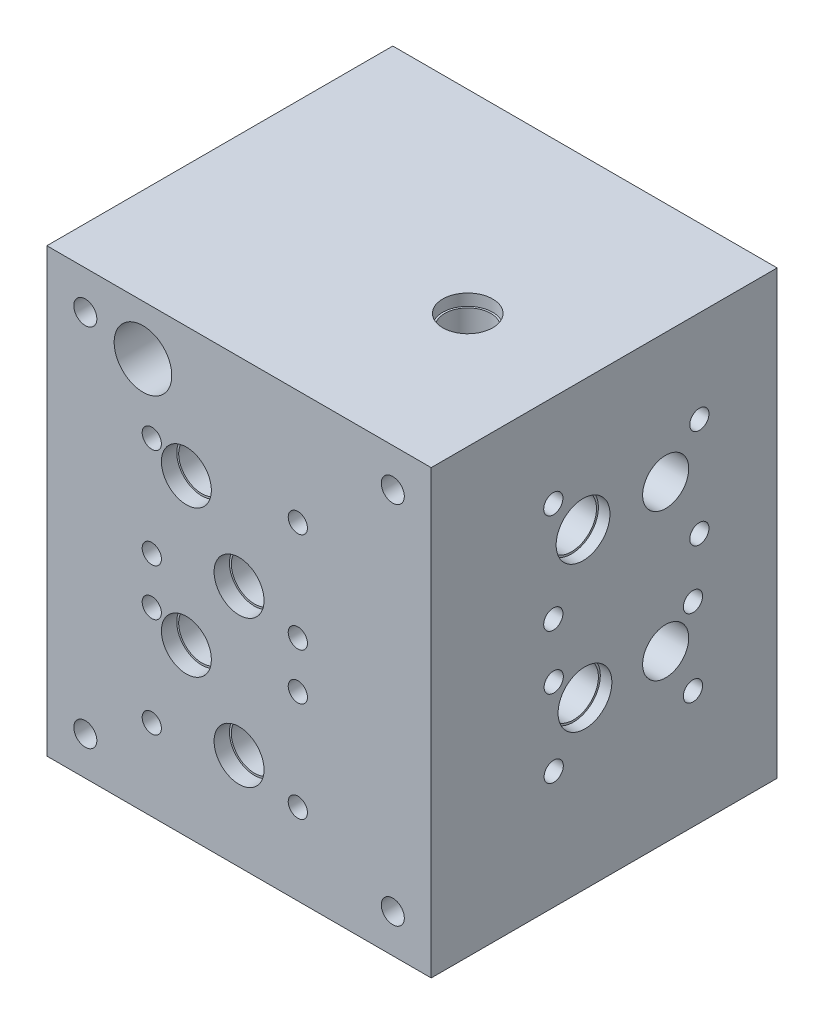
SolidWorks part; units mm, degrees
ref_plane "前视基准面" through (0, 0, 0) normal (0, 0, 1) x (1, 0, 0)
ref_plane "上视基准面" through (0, 0, 0) normal (0, 1, 0) x (1, 0, 0)
ref_plane "右视基准面" through (0, 0, 0) normal (1, 0, 0) x (0, 0, -1)
other "Configuration Table"
sketch "草图1" plane through (0, 0, 0) normal (0, 0, 1) x (1, 0, 0)
  line L1 (-100, -100) -> (100, -100)
  line L2 (-100, -100) -> (-100, 100)
  line L3 (-100, 100) -> (100, 100)
  line L4 (100, -100) -> (100, 100)
  line L5 (-100, -100) -> (100, 100) construction
  line L6 (-100, 100) -> (100, -100) construction
  point P0 (0, 0)
  dimension "D1" = 200
  dimension "D2" = 200
extrude "凸台-拉伸1" add sketch "草图1" along normal blind 180
sketch "草图2" plane through (0, 0, 0) normal (0, 0, -1) x (-1, 0, 0)
  line L0 (-100, -100) -> (-100, 100) construction
  line L3 (100, -100) -> (-100, -100) construction
  line L4 (100, 100) -> (100, -100) construction
  point P0 (-80, 110)
  point P1 (80, 110)
  point P2 (-80, -80)
  point P3 (80, -80)
  point P6 (50, 104)
  dimension "D1" = 20
  dimension "D2" = 210
  dimension "D3" = 210
  dimension "D4" = 20
  dimension "D5" = 20
  dimension "D6" = 20
  dimension "D7" = 20
  dimension "D8" = 20
  dimension "D9" = 50
  dimension "D10" = 204
hole_wizard "M14 螺纹孔1" positions "草图3" profile "草图5" tap size "M14" standard "GB" end condition through all
sketch "草图3" plane through (0, 0, 0) normal (0, 0, -1) x (-1, 0, 0)
  point P0 (-80, 110)
  point P3 (80, 110)
  point P6 (80, -80)
  point P9 (-80, -80)
sketch "草图5" plane through (80, 110, 0) normal (1, 0, 0) x (0, 1, 0)
  line L0 (0, 0) -> (0, 180)
  line L1 (0, 180) -> (6, 180)
  line L2 (6, 180) -> (6, 0)
  line L5 (6, 0) -> (0, 0)
  line L11 (0, -6.35) -> (0, 107.95) construction
  dimension "通孔螺纹孔钻头直径" = 12
  dimension "通孔螺纹孔钻头深度" = 180
cosmetic thread "孔螺蚊线1" parameters "D2"=14
cosmetic thread "孔螺蚊线2" parameters "D2"=14
sketch "草图9" plane through (0, 0, 0) normal (0, 0, -1) x (-1, 0, 0)
  line L0 (100, -100) -> (-100, -100) construction
  line L2 (-100, -100) -> (-100, 100) construction
  point P0 (0, -70)
  dimension "D1" = 30
  dimension "D2" = 100
hole_wizard "M14 六角头螺栓的柱形沉头孔2" positions "草图19" profile "草图20" counterbore size "M14" standard "GB"
sketch "草图19" plane through (0, 0, 0) normal (0, 0, -1) x (-1, 0, 0)
  point P0 (0, -70)
sketch "草图20" plane through (0, -70, 0) normal (1, 0, 0) x (0, 1, 0)
  line L0 (0, 0) -> (0, 68)
  line L1 (0, 68) -> (12, 60.7897)
  line L2 (12, 60.7897) -> (12, 8)
  line L3 (12, 8) -> (13, 8)
  line L4 (13, 8) -> (13, 0)
  line L5 (13, 0) -> (0, 0)
  line L10 (0, 68) -> (-12, 60.7897) construction
  line L11 (0, -6.35) -> (0, 107.95) construction
  dimension "孔直径" = 24
  dimension "孔深度" = 68
  dimension "柱形沉头孔直径" = 26
  dimension "柱形沉头孔深度" = 8
  dimension "导头角度" = 118
sketch "草图21" plane through (0, -100, 0) normal (0, -1, 0) x (1, 0, 0)
  point P0 (0, 49.309)
hole_wizard "M16 六角头螺栓的柱形沉头孔2" positions "草图22" profile "草图23" counterbore size "M16" standard "GB"
sketch "草图22" plane through (0, -100, 0) normal (0, -1, 0) x (-1, 0, 0)
  point P0 (0, -49.309)
sketch "草图23" plane through (0, -100, 49.309) normal (1, 0, 0) x (0, 0, -1)
  line L0 (0, 0) -> (0, 40)
  line L1 (0, 40) -> (11, 33.3905)
  line L2 (11, 33.3905) -> (11, 6)
  line L3 (11, 6) -> (12, 6)
  line L4 (12, 6) -> (12, 0)
  line L5 (12, 0) -> (0, 0)
  line L10 (0, 40) -> (-11, 33.3905) construction
  line L11 (0, -6.35) -> (0, 107.95) construction
  dimension "孔直径" = 22
  dimension "孔深度" = 40
  dimension "柱形沉头孔直径" = 24
  dimension "柱形沉头孔深度" = 6
  dimension "导头角度" = 118
sketch "草图24" plane through (0, -100, 0) normal (0, -1, 0) x (1, 0, 0)
  line L0 (-100, 180) -> (-100, 0) construction
  line L1 (100, 180) -> (100, 0) construction
  line L2 (-100, 0) -> (100, 0) construction
  point P0 (-52, 80)
  point P1 (52, 80)
  point P8 (-52, 35)
  point P9 (52, 35)
  point P10 (0, 89.309)
  dimension "D1" = 48
  dimension "D2" = 48
  dimension "D3" = 80
  dimension "D4" = 80
  dimension "D5" = 45
  dimension "D6" = 45
  dimension "D7" = 40
hole_wizard "M12 螺纹孔1" positions "草图25" profile "草图26" tap size "M12" standard "GB"
sketch "草图25" plane through (0, -100, 0) normal (0, -1, 0) x (-1, 0, 0)
  point P0 (-52, -80)
  point P3 (52, -80)
  point P6 (52, -35)
  point P9 (-52, -35)
cosmetic thread "孔螺蚊线5" parameters "D1"=24, "D2"=12
cosmetic thread "孔螺蚊线6" parameters "D1"=24, "D2"=12
cosmetic thread "孔螺蚊线7" parameters "D1"=24, "D2"=12
cosmetic thread "孔螺蚊线8" parameters "D1"=24, "D2"=12
sketch "草图26" plane through (52, -100, 80) normal (1, 0, 0) x (0, 0, -1)
  line L0 (0, 0) -> (0, 20)
  line L1 (0, 20) -> (5.1, 16.9356)
  line L2 (5.1, 16.9356) -> (5.1, 0)
  line L5 (5.1, 0) -> (0, 0)
  line L10 (0, 20) -> (-5.1, 16.9356) construction
  line L11 (0, -6.35) -> (0, 107.95) construction
  dimension "螺纹孔钻头直径" = 10.2
  dimension "螺纹孔钻头深度" = 20
  dimension "导头角度" = 118
hole_wizard "M16 六角头螺栓的柱形沉头孔3" positions "草图28" profile "草图29" counterbore size "M16" standard "GB"
sketch "草图28" plane through (0, -100, 0) normal (0, -1, 0) x (-1, 0, 0)
  point P0 (0, -89.309)
sketch "草图29" plane through (0, -100, 89.309) normal (1, 0, 0) x (0, 0, -1)
  line L0 (0, 0) -> (0, 144)
  line L1 (0, 144) -> (12, 136.7897)
  line L2 (12, 136.7897) -> (12, 6)
  line L3 (12, 6) -> (13, 6)
  line L4 (13, 6) -> (13, 0)
  line L5 (13, 0) -> (0, 0)
  line L10 (0, 144) -> (-12, 136.7897) construction
  line L11 (0, -6.35) -> (0, 107.95) construction
  dimension "孔直径" = 24
  dimension "孔深度" = 144
  dimension "柱形沉头孔直径" = 26
  dimension "柱形沉头孔深度" = 6
  dimension "导头角度" = 118
sketch "草图31" plane through (0, 0, 180) normal (0, 0, 1) x (1, 0, 0)
  line L1 (-52.4052, 77.5676) -> (37.5948, 77.5676)
  line L2 (-52.4052, 77.5676) -> (-52.4052, 11.5676)
  line L3 (-52.4052, 11.5676) -> (37.5948, 11.5676)
  line L4 (37.5948, 77.5676) -> (37.5948, 11.5676)
  line L5 (-52.4052, 1.2935) -> (37.5948, 1.2935)
  line L6 (-52.4052, 1.2935) -> (-52.4052, -64.7065)
  line L7 (-52.4052, -64.7065) -> (37.5948, -64.7065)
  line L8 (37.5948, 1.2935) -> (37.5948, -64.7065)
  point P8 (-45.4052, 70.5676)
  point P9 (30.5948, 70.5676)
  point P10 (-45.4052, 18.5676)
  point P11 (30.5948, 18.5676)
  point P12 (30.5948, -5.7065)
  point P13 (30.5948, -57.7065)
  point P14 (-45.4052, -57.7065)
  point P15 (0, -49.7065)
  point P16 (-45.4052, -5.7065)
  point P17 (-27.4052, -13.7065)
  point P18 (0, 26.5676)
  point P19 (-27.4052, 62.5676)
  dimension "D1" = 66
  dimension "D2" = 66
  dimension "D3" = 90
  dimension "D4" = 90
  dimension "D5" = 7
  dimension "D6" = 7
  dimension "D7" = 7
  dimension "D8" = 7
  dimension "D9" = 7
  dimension "D10" = 7
  dimension "D11" = 7
  dimension "D12" = 7
  dimension "D13" = 7
  dimension "D14" = 7
  dimension "D15" = 7
  dimension "D16" = 7
  dimension "D17" = 15
  dimension "D18" = 15
  dimension "D19" = 15
  dimension "D20" = 15
  dimension "D21" = 25
  dimension "D22" = 25
hole_wizard "M12 螺纹孔2" positions "草图32" profile "草图33" tap size "M12" standard "GB"
sketch "草图32" plane through (0, 0, 180) normal (0, 0, 1) x (1, 0, 0)
  point P0 (-45.4052, 70.5676)
  point P3 (30.5948, 70.5676)
  point P6 (30.5948, 18.5676)
  point P9 (-45.4052, 18.5676)
  point P12 (-45.4052, -5.7065)
  point P15 (-45.4052, -57.7065)
  point P18 (30.5948, -5.7065)
  point P21 (30.5948, -57.7065)
sketch "草图33" plane through (-45.4052, 70.5676, 180) normal (1, 0, 0) x (0, -1, 0)
  line L0 (0, 0) -> (0, 20)
  line L1 (0, 20) -> (5, 16.9957)
  line L2 (5, 16.9957) -> (5, 0)
  line L5 (5, 0) -> (0, 0)
  line L10 (0, 20) -> (-5, 16.9957) construction
  line L11 (0, -6.35) -> (0, 107.95) construction
  dimension "螺纹孔钻头直径" = 10
  dimension "螺纹孔钻头深度" = 20
  dimension "导头角度" = 118
cosmetic thread "孔螺蚊线9" parameters "D1"=24, "D2"=12
cosmetic thread "孔螺蚊线10" parameters "D1"=24, "D2"=12
cosmetic thread "孔螺蚊线11" parameters "D1"=24, "D2"=12
cosmetic thread "孔螺蚊线12" parameters "D1"=24, "D2"=12
cosmetic thread "孔螺蚊线13" parameters "D1"=24, "D2"=12
cosmetic thread "孔螺蚊线14" parameters "D1"=24, "D2"=12
cosmetic thread "孔螺蚊线15" parameters "D1"=24, "D2"=12
cosmetic thread "孔螺蚊线16" parameters "D1"=24, "D2"=12
hole_wizard "M14 六角头螺栓的柱形沉头孔3" positions "草图40" profile "草图41" counterbore size "M14" standard "GB"
sketch "草图40" plane through (0, 0, 180) normal (0, 0, 1) x (1, 0, 0)
  point P0 (0, -49.7065)
  point P6 (0, 26.5676)
sketch "草图41" plane through (0, -49.7065, 180) normal (1, 0, 0) x (0, -1, 0)
  line L0 (0, 0) -> (0, 98)
  line L1 (0, 98) -> (12, 90.7897)
  line L2 (12, 90.7897) -> (12, 8)
  line L3 (12, 8) -> (13, 8)
  line L4 (13, 8) -> (13, 0)
  line L5 (13, 0) -> (0, 0)
  line L10 (0, 98) -> (-12, 90.7897) construction
  line L11 (0, -6.35) -> (0, 107.95) construction
  dimension "孔直径" = 24
  dimension "孔深度" = 98
  dimension "柱形沉头孔直径" = 26
  dimension "柱形沉头孔深度" = 8
  dimension "导头角度" = 118
hole_wizard "M14 六角头螺栓的柱形沉头孔4" positions "草图42" profile "草图43" counterbore size "M14" standard "GB"
sketch "草图42" plane through (0, 0, 180) normal (0, 0, 1) x (1, 0, 0)
  point P0 (-27.4052, 62.5676)
  point P3 (-27.4052, -13.7065)
sketch "草图43" plane through (-27.4052, 62.5676, 180) normal (1, 0, 0) x (0, -1, 0)
  line L0 (0, 0) -> (0, 78)
  line L1 (0, 78) -> (12, 70.7897)
  line L2 (12, 70.7897) -> (12, 8)
  line L3 (12, 8) -> (13, 8)
  line L4 (13, 8) -> (13, 0)
  line L5 (13, 0) -> (0, 0)
  line L10 (0, 78) -> (-12, 70.7897) construction
  line L11 (0, -6.35) -> (0, 107.95) construction
  dimension "孔直径" = 24
  dimension "孔深度" = 78
  dimension "柱形沉头孔直径" = 26
  dimension "柱形沉头孔深度" = 8
  dimension "导头角度" = 118
sketch "草图44" plane through (-100, 0, 0) normal (-1, 0, 0) x (0, 0, 1)
  line L0 (180, 77.5676) -> (180, 11.5676) construction
  line L1 (180, 1.2935) -> (180, -64.7065) construction
  point P0 (113, 62.5676)
  point P1 (113, -13.7065)
  dimension "D1" = 67
  dimension "D2" = 67
hole_wizard "M16 六角头螺栓的柱形沉头孔4" positions "草图45" profile "草图46" counterbore size "M16" standard "GB"
sketch "草图45" plane through (-100, 0, 0) normal (-1, 0, 0) x (0, 0, 1)
  point P0 (113, 62.5676)
  point P3 (113, -13.7065)
sketch "草图46" plane through (-100, 62.5676, 113) normal (0, 1, 0) x (0, 0, 1)
  line L0 (0, 0) -> (0, 90)
  line L1 (0, 90) -> (12, 82.7897)
  line L2 (12, 82.7897) -> (12, 6)
  line L3 (12, 6) -> (13, 6)
  line L4 (13, 6) -> (13, 0)
  line L5 (13, 0) -> (0, 0)
  line L10 (0, 90) -> (-12, 82.7897) construction
  line L11 (0, -6.35) -> (0, 107.95) construction
  dimension "孔直径" = 24
  dimension "孔深度" = 90
  dimension "柱形沉头孔直径" = 26
  dimension "柱形沉头孔深度" = 6
  dimension "导头角度" = 118
sketch "草图47" plane through (0, 100, 0) normal (0, 1, 0) x (1, 0, 0)
  line L1 (-100, 0) -> (100, 0)
  line L2 (-100, 0) -> (-100, -180)
  line L3 (-100, -180) -> (100, -180)
  line L4 (100, 0) -> (100, -180)
sketch "草图48" plane through (0, 100, 0) normal (0, 1, 0) x (1, 0, 0)
  line L1 (-100, 0) -> (100, 0)
  line L2 (-100, 0) -> (-100, -180)
  line L3 (-100, -180) -> (100, -180)
  line L4 (100, 0) -> (100, -180)
extrude "凸台-拉伸3" add sketch "草图48" along normal blind 30
hole_wizard "M14 螺纹孔2" positions "草图49" profile "草图50" tap size "M14" standard "GB" end condition through all
sketch "草图49" plane through (0, 0, 0) normal (0, 0, -1) x (-1, 0, 0)
  point P0 (-80, 110)
  point P3 (80, 110)
sketch "草图50" plane through (80, 110, 0) normal (1, 0, 0) x (0, 1, 0)
  line L0 (0, 0) -> (0, 180)
  line L1 (0, 180) -> (6, 180)
  line L2 (6, 180) -> (6, 0)
  line L5 (6, 0) -> (0, 0)
  line L11 (0, -6.35) -> (0, 107.95) construction
  dimension "通孔螺纹孔钻头直径" = 12
  dimension "通孔螺纹孔钻头深度" = 180
cosmetic thread "孔螺蚊线17" parameters "D2"=14
cosmetic thread "孔螺蚊线18" parameters "D2"=14
hole_wizard "M14 六角头螺栓的柱形沉头孔6" positions "草图53" profile "草图54" counterbore size "M14" standard "GB" end condition through all
sketch "草图53" plane through (0, 0, 0) normal (0, 0, -1) x (-1, 0, 0)
  point P0 (50, 104)
sketch "草图54" plane through (-50, 104, 0) normal (1, 0, 0) x (0, 1, 0)
  line L0 (0, 0) -> (0, 180)
  line L1 (0, 180) -> (15, 180)
  line L3 (15, 180) -> (15, 14)
  line L4 (15, 14) -> (17, 14)
  line L5 (17, 14) -> (17, 0)
  line L7 (17, 0) -> (0, 0)
  line L11 (0, -6.35) -> (0, 107.95) construction
  dimension "通孔孔直径" = 30
  dimension "通孔孔深度" = 180
  dimension "柱形沉头孔直径" = 34
  dimension "柱形沉头孔深度" = 14
sketch "草图55" plane through (-100, 0, 0) normal (-1, 0, 0) x (0, 0, 1)
  point P0 (58, 62.5676)
  point P1 (58, -13.7065)
  dimension "D1" = 55
  dimension "D2" = 55
hole_wizard "M16 六角头螺栓的柱形沉头孔5" positions "草图56" profile "草图57" counterbore size "M16" standard "GB" end condition through all
sketch "草图56" plane through (-100, 0, 0) normal (-1, 0, 0) x (0, 0, 1)
  point P0 (58, 62.5676)
  point P3 (58, -13.7065)
sketch "草图57" plane through (-100, 62.5676, 58) normal (0, 1, 0) x (0, 0, 1)
  line L0 (0, 0) -> (0, 200)
  line L1 (0, 200) -> (12, 200)
  line L3 (12, 200) -> (12, 6)
  line L4 (12, 6) -> (13, 6)
  line L5 (13, 6) -> (13, 0)
  line L7 (13, 0) -> (0, 0)
  line L11 (0, -6.35) -> (0, 107.95) construction
  dimension "通孔孔直径" = 24
  dimension "通孔孔深度" = 200
  dimension "柱形沉头孔直径" = 26
  dimension "柱形沉头孔深度" = 6
sketch "草图60" plane through (-100, 0, 0) normal (-1, 0, 0) x (0, 0, 1)
  line L1 (136.144, -45.6939) -> (36.7889, -45.6939)
  line L2 (136.144, -45.6939) -> (136.144, 85.2553)
  line L3 (136.144, 85.2553) -> (36.7889, 85.2553)
  line L4 (36.7889, -45.6939) -> (36.7889, 85.2553)
  line L5 (136.144, -45.6939) -> (36.7889, 85.2553) construction
  line L6 (136.144, 85.2553) -> (36.7889, -45.6939) construction
  point P0 (86.4664, 19.7807)
sketch "草图61" plane through (100, 0, 0) normal (1, 0, 0) x (0, 0, -1)
  arc A0 (-123.1949, 56.238) -> (-123.1949, 68.8973) centre (-113, 62.5676) ccw construction
  arc A1 (-123.1949, -20.0361) -> (-123.1949, -7.3768) centre (-113, -13.7065) ccw construction
  point P0 (-101, 62.5676)
  point P1 (-101, -13.7065)
hole_wizard "M16 六角头螺栓的柱形沉头孔6" positions "草图62" profile "草图63" counterbore size "M16" standard "GB"
sketch "草图62" plane through (100, 0, 0) normal (1, 0, 0) x (0, 0, -1)
  circle A0 centre (-113, -13.7065) radius 13 construction
  point P0 (-101, 62.5676)
  point P3 (-100, -13.7065)
sketch "草图63" plane through (100, 62.5676, 101) normal (0, 1, 0) x (0, 0, -1)
  line L0 (0, 0) -> (0, 80)
  line L1 (0, 80) -> (13, 72.1888)
  line L2 (13, 72.1888) -> (13, 6)
  line L3 (13, 6) -> (14, 6)
  line L4 (14, 6) -> (14, 0)
  line L5 (14, 0) -> (0, 0)
  line L10 (0, 80) -> (-13, 72.1888) construction
  line L11 (0, -6.35) -> (0, 107.95) construction
  dimension "孔直径" = 26
  dimension "孔深度" = 80
  dimension "柱形沉头孔直径" = 28
  dimension "柱形沉头孔深度" = 6
  dimension "导头角度" = 118
sketch "草图64" plane through (100, 0, 0) normal (1, 0, 0) x (0, 0, -1)
  line L0 (-180, 89) -> (-14, 89) construction
  line L1 (-33.4648, 23) -> (-123.4648, 23)
  line L2 (-33.4648, 23) -> (-33.4648, 89)
  line L3 (-33.4648, 89) -> (-123.4648, 89)
  line L4 (-123.4648, 23) -> (-123.4648, 89)
  line L5 (-33.4648, 23) -> (-123.4648, 89) construction
  line L6 (-33.4648, 89) -> (-123.4648, 23) construction
  line L7 (-136.144, -45.6939) -> (-36.7889, -45.6939) construction
  line L8 (-33.2553, -57.4435) -> (-123.2553, -57.4435)
  line L9 (-33.2553, -57.4435) -> (-33.2553, 8.5565)
  line L10 (-33.2553, 8.5565) -> (-123.2553, 8.5565)
  line L11 (-123.2553, -57.4435) -> (-123.2553, 8.5565)
  line L12 (-33.2553, -57.4435) -> (-123.2553, 8.5565) construction
  line L13 (-33.2553, 8.5565) -> (-123.2553, -57.4435) construction
  line L14 (-36.7889, -45.6939) -> (-36.7889, 85.2553) construction
  point P0 (-78.4648, 56)
  point P7 (-78.2553, -24.4435)
  point P12 (-116.4648, 82)
  point P13 (-116.4648, 30)
  point P14 (-40.4648, 30.4949)
  point P15 (-40.4648, 82)
  point P16 (-116.2553, 1.5565)
  point P17 (-43.7889, 1.5565)
  point P18 (-116.2553, -38.6939)
  point P19 (-43.7889, -38.6939)
  dimension "D1" = 90
  dimension "D2" = 66
  dimension "D3" = 90
  dimension "D4" = 66
  dimension "D5" = 7
  dimension "D6" = 7
  dimension "D7" = 7
  dimension "D8" = 7.4949
  dimension "D9" = 7
  dimension "D10" = 7
  dimension "D11" = 7
  dimension "D12" = 7
  dimension "D13" = 7
  dimension "D14" = 7
  dimension "D15" = 7
  dimension "D16" = 7
  dimension "D17" = 7
  dimension "D18" = 7
  dimension "D19" = 7
hole_wizard "M12 螺纹孔3" positions "草图65" profile "草图66" tap size "M12" standard "GB"
sketch "草图65" plane through (100, 0, 0) normal (1, 0, 0) x (0, 0, -1)
  point P0 (-116.4648, 30)
  point P3 (-116.4648, 82)
  point P6 (-40.4648, 82)
  point P9 (-40.4648, 30.4949)
  point P12 (-43.7889, -38.6939)
  point P15 (-116.2553, -38.6939)
  point P18 (-116.2553, 1.5565)
  point P21 (-43.7889, 1.5565)
sketch "草图66" plane through (100, 30, 116.4648) normal (0, 1, 0) x (0, 0, -1)
  line L0 (0, 0) -> (0, 32.75)
  line L1 (0, 32.75) -> (5, 29.7457)
  line L2 (5, 29.7457) -> (5, 0)
  line L5 (5, 0) -> (0, 0)
  line L10 (0, 32.75) -> (-5, 29.7457) construction
  line L11 (0, -6.35) -> (0, 107.95) construction
  dimension "螺纹孔钻头直径" = 10
  dimension "螺纹孔钻头深度" = 32.75
  dimension "导头角度" = 118
cosmetic thread "孔螺蚊线19" parameters "D1"=24, "D2"=12
cosmetic thread "孔螺蚊线20" parameters "D1"=24, "D2"=12
cosmetic thread "孔螺蚊线21" parameters "D1"=24, "D2"=12
cosmetic thread "孔螺蚊线22" parameters "D1"=24, "D2"=12
cosmetic thread "孔螺蚊线23" parameters "D1"=24, "D2"=12
cosmetic thread "孔螺蚊线24" parameters "D1"=24, "D2"=12
cosmetic thread "孔螺蚊线25" parameters "D1"=24, "D2"=12
cosmetic thread "孔螺蚊线26" parameters "D1"=24, "D2"=12
sketch "草图68" plane through (0, 130, 0) normal (0, 1, 0) x (1, 0, 0)
  point P0 (40, -101)
  dimension "D1" = 20
hole_wizard "M16 六角头螺栓的柱形沉头孔7" positions "草图69" profile "草图70" counterbore size "M16" standard "GB"
sketch "草图69" plane through (0, 130, 0) normal (0, 1, 0) x (1, 0, 0)
  point P0 (40, -101)
sketch "草图70" plane through (40, 130, 101) normal (1, 0, 0) x (0, 0, 1)
  line L0 (0, 0) -> (0, 164)
  line L1 (0, 164) -> (12, 156.7897)
  line L2 (12, 156.7897) -> (12, 6)
  line L3 (12, 6) -> (13, 6)
  line L4 (13, 6) -> (13, 0)
  line L5 (13, 0) -> (0, 0)
  line L10 (0, 164) -> (-12, 156.7897) construction
  line L11 (0, -6.35) -> (0, 107.95) construction
  dimension "孔直径" = 24
  dimension "孔深度" = 164
  dimension "柱形沉头孔直径" = 26
  dimension "柱形沉头孔深度" = 6
  dimension "导头角度" = 118
